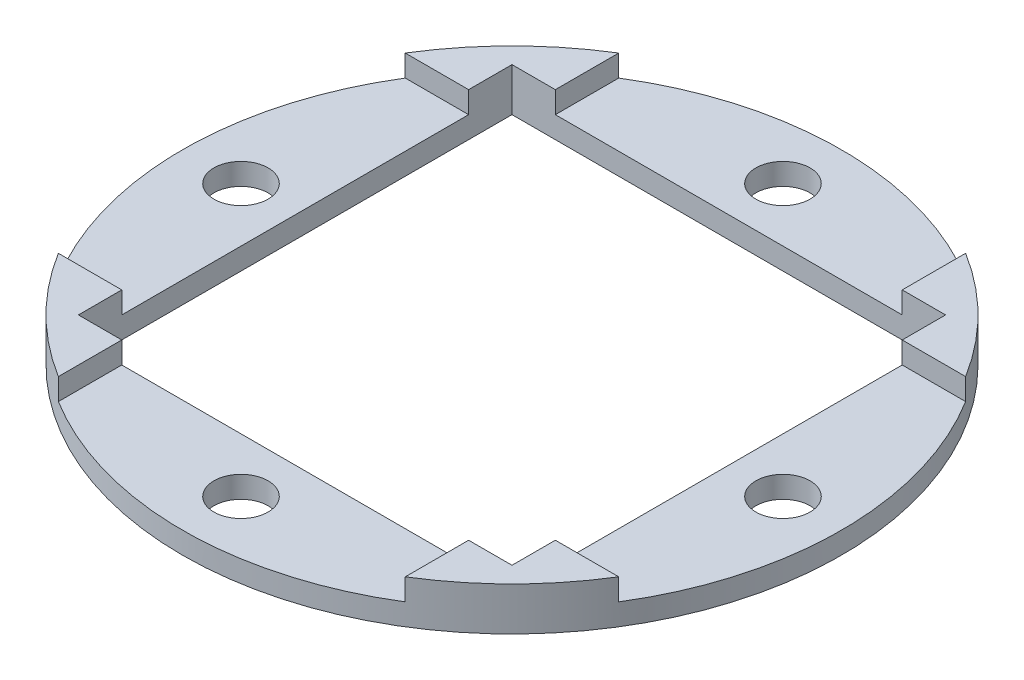
SolidWorks part; units mm, degrees
material "Custom Plastic"
ref_plane "Front Plane" through (0, 0, 0) normal (0, 0, 1) x (1, 0, 0)
ref_plane "Top Plane" through (0, 0, 0) normal (0, 1, 0) x (1, 0, 0)
ref_plane "Right Plane" through (0, 0, 0) normal (1, 0, 0) x (0, 0, -1)
sketch "Sketch1" plane through (0, 0, 0) normal (0, 1, 0) x (1, 0, 0)
  line L0 (0, 0) -> (0, -17.9724) construction
  line L1 (-50, -50) -> (50, -50)
  line L2 (-50, -50) -> (-50, 50)
  line L3 (-50, 50) -> (50, 50)
  line L4 (50, -50) -> (50, 50)
  line L5 (-50, -50) -> (50, 50) construction
  line L6 (-50, 50) -> (50, -50) construction
  line L7 (0, 0) -> (14.9739, 0) construction
  line L8 (0, 62.5) -> (14.3316, 62.5) construction
  line L9 (0, 76) -> (25.822, 76) construction
  circle A0 centre (0, 0) radius 76
  circle A1 centre (0, 0) radius 62.5 construction
  circle A2 centre (0, 62.5) radius 5
  circle A3 centre (62.5, 0) radius 5
  circle A4 centre (0, -62.5) radius 5
  circle A5 centre (-62.5, 0) radius 5
  dimension "D1" = 152
  dimension "D4" = 125
  dimension "D5" = 10
  dimension "D2" = 100
  dimension "D3" = 100
extrude "Boss-Extrude1" add sketch "Sketch1" along normal blind 5 contours A0 | L2 L1 L4 L3
sketch "Sketch2" plane through (0, 5, 0) normal (0, 1, 0) x (1, 0, 0)
  circle A0 centre (0, 0) radius 62.5 construction
  circle A1 centre (-62.5, 0) radius 6.25
  circle A2 centre (0, 62.5) radius 6.25
  circle A3 centre (62.5, 0) radius 6.25
  circle A4 centre (0, -62.5) radius 6.25
  dimension "D1" = 125
  dimension "D3" = 12.5
extrude "Cut-Extrude1" cut sketch "Sketch2" against normal blind 10
sketch "Sketch3" plane through (0, 5, 0) normal (0, 1, 0) x (1, 0, 0)
  line L0 (-50, -50) -> (-40, -50)
  line L3 (-40, -50) -> (-50, -50)
  line L4 (-50, -40) -> (-50, -50)
  line L5 (0, 0) -> (-85.3726, 0) construction
  line L6 (-50, 40) -> (-64.622, 40)
  line L7 (-50, -50) -> (-50, -40)
  line L8 (-50, -40) -> (-64.622, -40)
  line L9 (-40, -50) -> (-40, -64.622)
  line L10 (-50, 40) -> (-50, 50)
  line L11 (-50, 50) -> (-40, 50)
  line L12 (-40, 50) -> (-40, 64.622)
  line L13 (0, 0) -> (0, -29.0709) construction
  line L14 (50, 40) -> (50, 50)
  line L15 (50, 50) -> (40, 50)
  line L16 (40, 50) -> (40, 64.622)
  line L17 (50, 40) -> (64.622, 40)
  line L18 (50, -50) -> (40, -50)
  line L19 (50, -40) -> (50, -50)
  line L20 (50, -40) -> (64.622, -40)
  line L21 (40, -50) -> (40, -64.622)
  arc A0 (-64.622, -40) -> (-40, -64.622) centre (0, 0) ccw
  circle A1 centre (0, 0) radius 76 construction
  arc A2 (-64.622, 40) -> (-40, 64.622) centre (0, 0) cw
  arc A3 (64.622, 40) -> (40, 64.622) centre (0, 0) ccw
  arc A4 (64.622, -40) -> (40, -64.622) centre (0, 0) cw
  line M11 (-50, 50) -> (50, 50)
  line M12 (50, 50) -> (50, -50)
  line M13 (50, -50) -> (-50, -50)
  line M14 (-50, -50) -> (-50, 50)
  circle M15 centre (0, 0) radius 76
  dimension "D1" = 10
  dimension "D2" = 10
extrude "Boss-Extrude2" add sketch "Sketch3" along normal blind 5 contours L21 L20 M13 M15 M12 | L9 L8 M13 M14 M15 | L12 L6 M11 M15 M14 | L17 L16 M12 M15 M11
